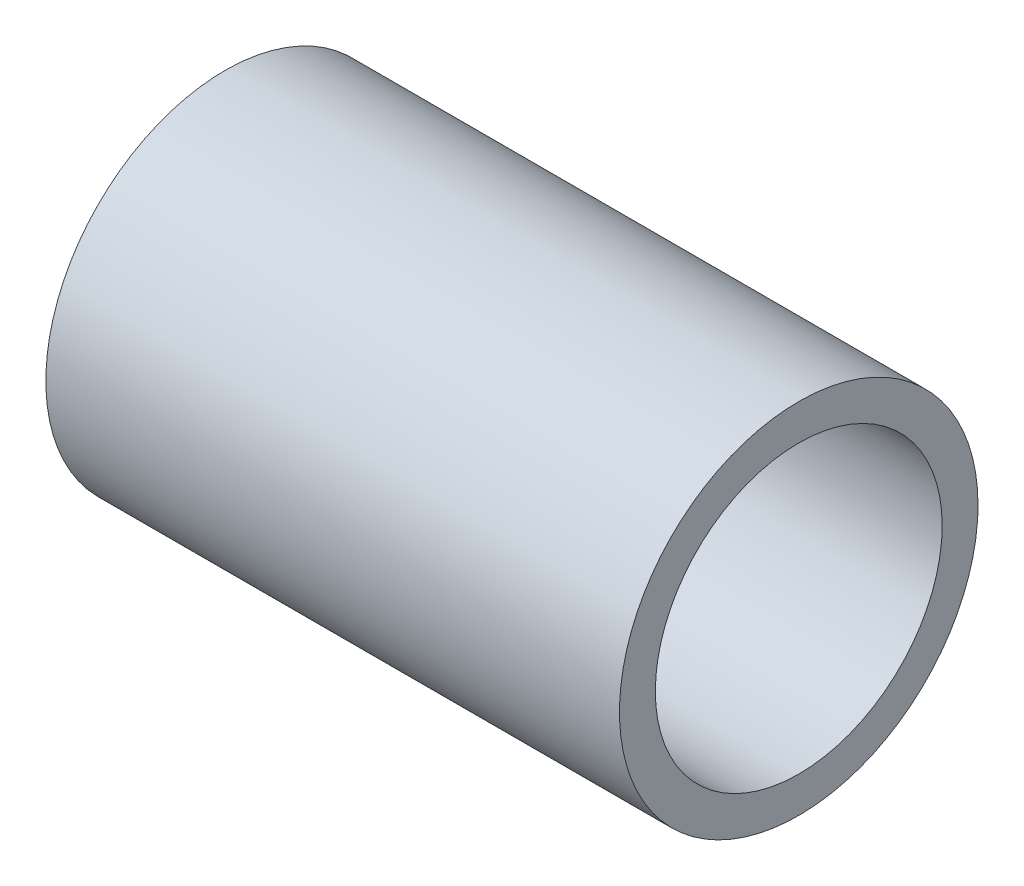
SolidWorks part; units mm, degrees
ref_plane "Спереди" through (0, 0, 0) normal (0, 0, 1) x (1, 0, 0)
ref_plane "Сверху" through (0, 0, 0) normal (0, 1, 0) x (1, 0, 0)
ref_plane "Справа" through (0, 0, 0) normal (1, 0, 0) x (0, 0, -1)
sketch "Эскиз1" plane through (0, 0, 0) normal (1, 0, 0) x (0, 0, -1)
  circle A0 centre (0, 0) radius 25
  circle A1 centre (0, 0) radius 20
  dimension "D1" = 50
  dimension "D2" = 40
extrude "Бобышка-Вытянуть1" add sketch "Эскиз1" along normal blind 80
sketch "Эскиз2" plane through (0, 0, 0) normal (0, 0, 1) x (1, 0, 0)
  line L0 (0, 2) -> (0, -2)
  line L1 (5, -2) -> (5, 2)
  line L2 (5, 2) -> (0, 2)
  line L3 (0, 25) -> (0, -25) construction
  line L5 (0, -2) -> (5, -2)
extrude "Вырез-Вытянуть1" cut sketch "Эскиз2" against normal blind 80
